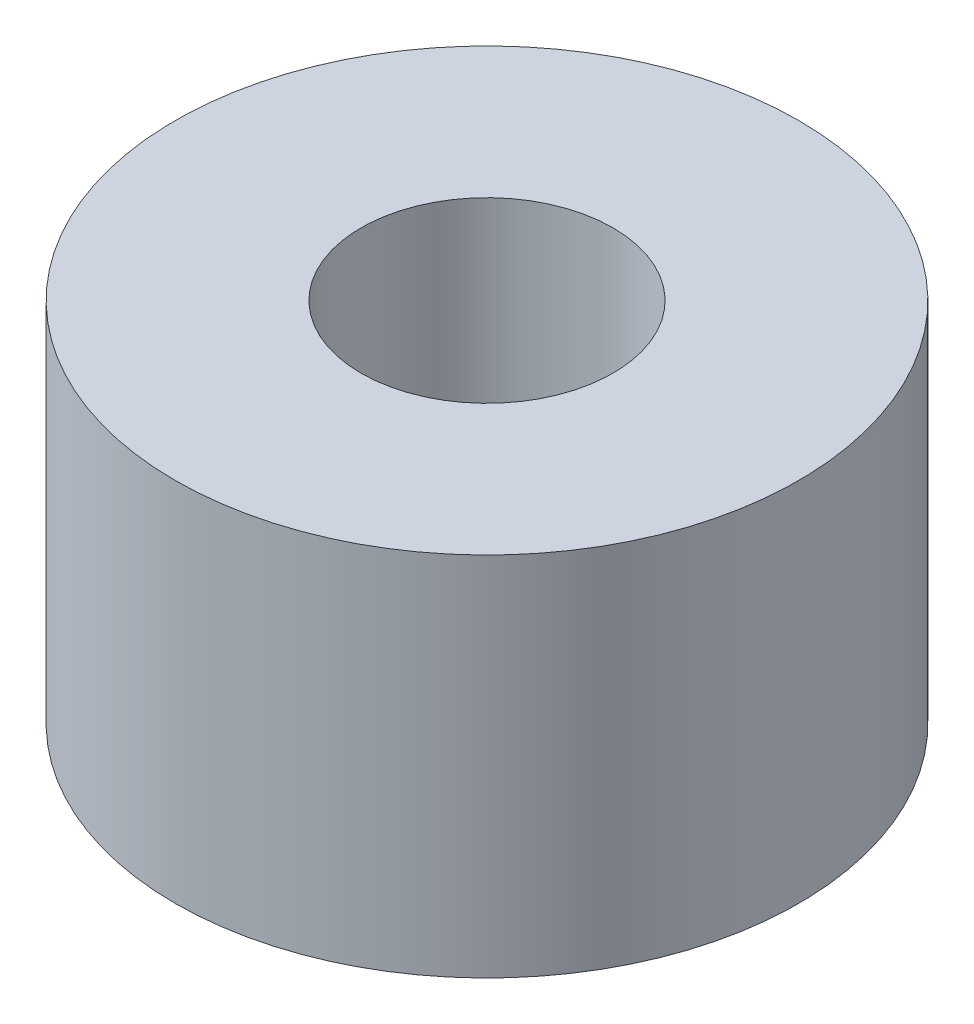
SolidWorks part; units mm, degrees
ref_plane "Front Plane" through (0, 0, 0) normal (0, 0, 1) x (1, 0, 0)
ref_plane "Top Plane" through (0, 0, 0) normal (0, 1, 0) x (1, 0, 0)
ref_plane "Right Plane" through (0, 0, 0) normal (1, 0, 0) x (0, 0, -1)
sketch "Sketch1" plane through (0, 0, 0) normal (0, 1, 0) x (1, 0, 0)
  circle A0 centre (0, 0) radius 4.95
  circle A1 centre (0, 0) radius 2
  dimension "D1" = 9.9
  dimension "D2" = 4
extrude "Boss-Extrude1" add sketch "Sketch1" along normal blind 5.8166
